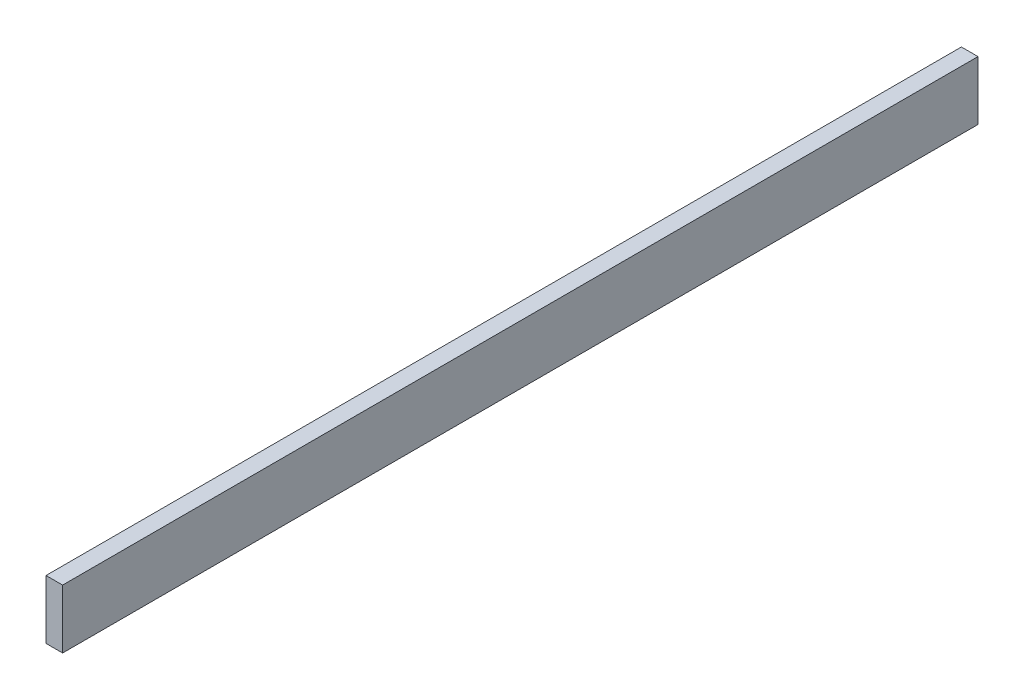
SolidWorks part; units mm, degrees
ref_plane "Front Plane" through (0, 0, 0) normal (0, 0, 1) x (1, 0, 0)
ref_plane "Top Plane" through (0, 0, 0) normal (0, 1, 0) x (1, 0, 0)
ref_plane "Right Plane" through (0, 0, 0) normal (1, 0, 0) x (0, 0, -1)
other "Configuration Table"
sketch "Sketch1" plane through (0, 0, 0) normal (0, 0, 1) x (1, 0, 0)
  line L1 (714, 1527) -> (726.7, 1527)
  line L2 (714, 1527) -> (714, 1572)
  line L3 (714, 1572) -> (726.7, 1572)
  line L4 (726.7, 1527) -> (726.7, 1572)
extrude "DET_MOTORLU_RAY_govde_45x12.7_1" add sketch "Sketch1" against normal blind 700 separate body
